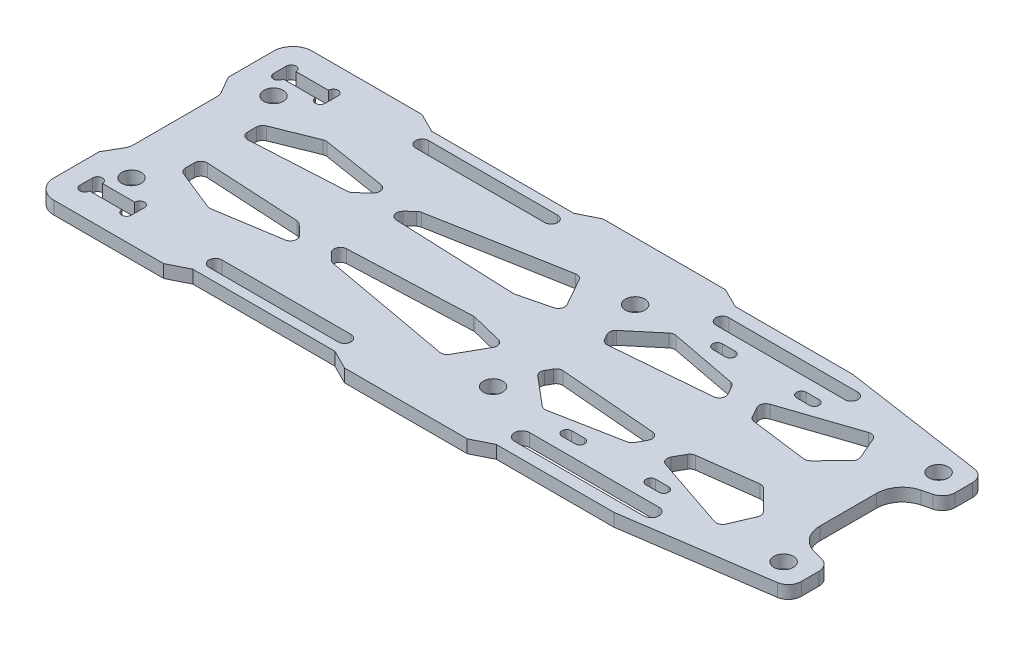
SolidWorks part; units mm, degrees
ref_plane "Front Plane" through (0, 0, 0) normal (0, 0, 1) x (1, 0, 0)
ref_plane "Top Plane" through (0, 0, 0) normal (0, 1, 0) x (1, 0, 0)
ref_plane "Right Plane" through (0, 0, 0) normal (1, 0, 0) x (0, 0, -1)
sketch "Sketch1" plane through (0, 0, 0) normal (0, 1, 0) x (1, 0, 0)
  line L0 (-46.6349, 20) -> (65.3651, 20)
  line L1 (-25.5638, -20) -> (-39.7059, -20)
  line L7 (-40.6349, 17) -> (15.3651, 17) construction
  line L8 (-40.6349, -17) -> (-40.6349, 17) construction
  line L9 (-40.6349, -17) -> (15.3651, -17) construction
  line L10 (15.3651, 17) -> (15.3651, -17) construction
  line L11 (-40.6349, 17) -> (15.3651, -17) construction
  line L12 (-40.6349, -17) -> (15.3651, 17) construction
  line L13 (65.3651, 20) -> (65.3651, -20)
  line L14 (65.3651, -20) -> (-25.5638, -20)
  line L15 (-46.6349, -20) -> (-46.6349, 20)
  line L16 (15.3651, 17) -> (61.3651, 17) construction
  line L17 (61.3651, 17) -> (61.3651, -17) construction
  line L18 (61.3651, -17) -> (15.3651, -17) construction
  line L19 (31.3651, -20) -> (65.3651, -15)
  line L20 (31.3651, 20) -> (65.3651, 15)
  line L21 (-46.6349, -14) -> (-35.6349, -14) construction
  line L22 (-46.6349, 14) -> (-35.6349, 14) construction
  line L23 (-35.6349, -14) -> (-35.6349, -16)
  line L24 (-35.6349, -16) -> (-43.6349, -16)
  line L25 (-43.6349, -16) -> (-43.6349, -14)
  line L30 (-39.7059, -20) -> (-46.6349, -20)
  line L45 (65.3651, -9) -> (59.3651, -7.5)
  line L46 (59.3651, -7.5) -> (59.3651, 7.5)
  line L47 (59.3651, 7.5) -> (65.3651, 9)
  line L48 (-35.6349, 14) -> (-35.6349, 16)
  line L49 (-35.6349, 16) -> (-43.6349, 16)
  line L50 (-43.6349, 16) -> (-43.6349, 14)
  line L51 (-43.6349, -14) -> (-35.6349, -14)
  line L52 (-43.6349, 14) -> (-35.6349, 14)
  line L53 (-44.909, -7) -> (-46.639, -10)
  line L54 (-44.909, 6.998) -> (-46.639, 10)
  line L55 (-44.909, -7) -> (-44.909, 6.998)
  circle A0 centre (15.3651, -11) radius 1.5
  circle A1 centre (15.3651, 11) radius 1.5
  arc A6 (-43.6349, -16) -> (-42.1349, -16) centre (-42.8849, -16) ccw
  arc A7 (-35.6349, -16) -> (-37.1349, -16) centre (-36.3849, -16) cw
  circle A8 centre (61.3651, -12) radius 1.5
  circle A9 centre (61.3651, 12) radius 1.5
  arc A18 (-35.6349, -14) -> (-37.1349, -14) centre (-36.3849, -14) ccw
  arc A19 (-43.6349, -14) -> (-42.1349, -14) centre (-42.8849, -14) cw
  arc A20 (-43.6349, 14) -> (-42.1349, 14) centre (-42.8849, 14) ccw
  arc A21 (-43.6349, 16) -> (-42.1349, 16) centre (-42.8849, 16) cw
  arc A22 (-35.6349, 16) -> (-37.1349, 16) centre (-36.3849, 16) ccw
  arc A23 (-35.6349, 14) -> (-37.1349, 14) centre (-36.3849, 14) cw
  circle A24 centre (-40.6349, -11) radius 1.5
  circle A25 centre (-40.6349, 11) radius 1.5
  point P0 (-12.6349, 0)
  point P5 (-12.6349, 0)
  dimension "D7" = 3
  dimension "D8" = 3
  dimension "D43" = 3
  dimension "D44" = 3
  dimension "D47" = 3
  dimension "D48" = 3
  dimension "D3" = 56
  dimension "D4" = 34
  dimension "D5" = 3
  dimension "D6" = 50
  dimension "D9" = 8
  dimension "D10" = 8
  dimension "D11" = 34
  dimension "D12" = 34
  dimension "D13" = 5
  dimension "D14" = 5
  dimension "D19" = 4
  dimension "D25" = 6
  dimension "D26" = 6
  dimension "D27" = 1.5
  dimension "D28" = 1.5
  dimension "D29" = 6
  dimension "D30" = 40
  dimension "D31" = 28
  dimension "D32" = 6
  dimension "D33" = 8
  dimension "D34" = 2
  dimension "D35" = 3
  dimension "D36" = 8
  dimension "D37" = 3
  dimension "D38" = 2
  dimension "D39" = 1.5
  dimension "D40" = 1.5
  dimension "D41" = 1.5
  dimension "D42" = 1.5
  dimension "D45" = 3
  dimension "D46" = 3
  dimension "D49" = 9
  dimension "D50" = 9
  dimension "D51" = 1
  dimension "D52" = 1
  dimension "D53" = 3.002
  dimension "D54" = 3
extrude "Boss-Extrude1" add sketch "Sketch1" along normal blind 2 contours L55 L53 L15 L30 L1 L14 L19 L13 L45 L46 L47 L20 L0 L54 A25 A24 A9 A8 A1 A0 L25 A19 L51 A18 L23 A7 L24 A6 L48 A23 L52 A20 L50 A21 L49 A22
fillet "Fillet1" radius 3 2 edges at (-46.6349, 1, -20) (-46.6349, 1, 20)
fillet "Fillet2" radius 2 4 edges at (65.3651, 1, -15) (65.3651, 1, -9) (65.3651, 1, 15) (65.3651, 1, 9)
fillet "Fillet3" radius 2 2 edges at (-44.909, 1, 7) (-44.909, 1, -6.998)
fillet "Fillet4" radius 4 2 edges at (59.3651, 1, 7.5) (59.3651, 1, -7.5)
sketch "Sketch3" plane through (0, 2, 0) normal (0, 1, 0) x (1, 0, 0)
  line L0 (-23.6349, 18.5) -> (-1.6349, 18.5)
  line L1 (-23.6349, -18.5) -> (-1.6349, -18.5)
  line L2 (31.3651, -20) -> (-43.6349, -20) construction
  line L3 (-26.6349, 20) -> (-23.6349, 18.5)
  line L4 (-43.6349, 20) -> (31.3651, 20) construction
  line L5 (-1.6349, 18.5) -> (1.3651, 20)
  line L6 (-26.6349, -20) -> (-23.6349, -18.5)
  line L7 (1.3651, -20) -> (-1.6349, -18.5)
  line L8 (-1.6349, -18.5) -> (-1.4114, -18.5)
  line L9 (-35.6349, -14) -> (-35.6349, -16) construction
  line L10 (-35.6349, 14) -> (-35.6349, 16) construction
  line L11 (-22.6349, 16) -> (-2.6349, 16) construction
  line L12 (-22.6349, 17) -> (-2.6349, 17)
  line L13 (-22.6349, 15) -> (-2.6349, 15)
  line L14 (-22.6349, -16) -> (-2.6349, -16) construction
  line L15 (-22.6349, -15) -> (-2.6349, -15)
  line L16 (-22.6349, -17) -> (-2.6349, -17)
  line L17 (23.3651, 18.5) -> (45.3651, 18.5)
  line L18 (23.3651, -18.5) -> (45.3651, -18.5)
  line L19 (20.3651, -20) -> (23.3651, -18.5)
  line L20 (23.3651, 18.5) -> (20.3651, 20)
  line L21 (20.3651, 20) -> (31.3651, 20)
  line L22 (31.3651, 20) -> (41.5651, 18.5)
  line L23 (31.3651, 20) -> (63.6561, 15.2513) construction
  line L24 (20.3651, -20) -> (31.3651, -20)
  line L25 (31.3651, -20) -> (41.5651, -18.5)
  line L26 (24.3651, -15.5) -> (44.3651, -15.5) construction
  line L27 (24.3651, -14.3269) -> (44.3651, -14.3269)
  line L28 (24.3651, -16.6731) -> (44.3651, -16.6731)
  line L29 (24.3651, 15.5) -> (44.3651, 15.5) construction
  line L30 (24.3651, 16.5) -> (44.3651, 16.5)
  line L31 (24.3651, 14.5) -> (44.3651, 14.5)
  line L32 (45.3651, 18.5) -> (41.5651, 18.5)
  line L33 (31.3651, -20) -> (63.6561, -15.2513) construction
  line L34 (41.5651, -18.5) -> (45.3651, -18.5)
  arc A0 (-22.6349, 17) -> (-22.6349, 15) centre (-22.6349, 16) ccw
  arc A1 (-2.6349, 15) -> (-2.6349, 17) centre (-2.6349, 16) ccw
  arc A2 (-22.6349, -15) -> (-22.6349, -17) centre (-22.6349, -16) ccw
  arc A3 (-2.6349, -17) -> (-2.6349, -15) centre (-2.6349, -16) ccw
  arc A4 (24.3651, -14.3269) -> (24.3651, -16.6731) centre (24.3651, -15.5) ccw
  arc A5 (44.3651, -16.6731) -> (44.3651, -14.3269) centre (44.3651, -15.5) ccw
  arc A6 (24.3651, 16.5) -> (24.3651, 14.5) centre (24.3651, 15.5) ccw
  arc A7 (44.3651, 14.5) -> (44.3651, 16.5) centre (44.3651, 15.5) ccw
  point P19 (-12.6349, 16)
  point P24 (-12.6349, -16)
  point P36 (34.3651, -15.5)
  point P52 (34.3651, 15.5)
  line M20 (63.6561, 15.2513) -> (31.3651, 20)
  line M21 (31.3651, 20) -> (-43.6349, 20)
  line M31 (-43.6349, -20) -> (31.3651, -20)
  line M32 (31.3651, -20) -> (63.6561, -15.2513)
  dimension "D12" = 1
  dimension "D14" = 1
  dimension "D1" = 37
  dimension "D2" = 1.5
  dimension "D3" = 12
  dimension "D4" = 12
  dimension "D5" = 3
  dimension "D6" = 3
  dimension "D7" = 3
  dimension "D8" = 3
  dimension "D9" = 22
  dimension "D10" = 22
  dimension "D11" = 2.5
  dimension "D13" = 2.5
  dimension "D15" = 1
  dimension "D16" = 20
  dimension "D17" = 20
  dimension "D18" = 1
  dimension "D19" = 1.5
  dimension "D20" = 3
  dimension "D21" = 3
  dimension "D22" = 25
  dimension "D23" = 22
  dimension "D24" = 22
  dimension "D25" = 25
  dimension "D26" = 3
  dimension "D27" = 1.5
  dimension "D28" = 1
  dimension "D29" = 20
  dimension "D30" = 20
  dimension "D31" = 1
  dimension "D32" = 3
extrude "Cut-Extrude1" cut sketch "Sketch3" against normal through all contours L28 A5 L27 A4 | L34 L18 L19 M32 M31 | L7 L1 L6 M31 | L16 A3 L15 A2 | L17 L32 L20 M20 M21 | L31 A7 L30 A6 | L0 L5 L3 M21 | L13 A1 L12 A0
sketch "Sketch6" plane through (0, 2, 0) normal (0, 1, 0) x (1, 0, 0)
  line L0 (-44.909, -0.0008) -> (59.3651, 0) construction
  line L1 (-44.909, -6.4647) -> (-44.909, 6.463) construction
  line L2 (59.3651, -4.3769) -> (59.3651, 4.3769) construction
  line L3 (-37.787, 3.0551) -> (-21.7169, 3.946)
  line L4 (-21.7169, 3.946) -> (-18.4542, 7.113)
  line L5 (-18.4542, 7.113) -> (-30.6285, 9.0449)
  line L6 (-30.6285, 9.0449) -> (-37.787, 6.1616)
  line L7 (-37.787, 6.1616) -> (-37.787, 3.0551)
  line L8 (-16.794, 3.946) -> (4.531, 3.0551)
  line L9 (4.531, 3.0551) -> (10.7399, 4.5891)
  line L10 (10.7399, 4.5891) -> (7.3326, 10.6474)
  line L11 (7.3326, 10.6474) -> (-13.8645, 6.7896)
  line L12 (-13.8645, 6.7896) -> (-16.794, 3.946)
  line L13 (17.9983, 3.3859) -> (16.7628, 5.5825)
  line L14 (16.7628, 5.5825) -> (22.1762, 10.1271)
  line L15 (22.1762, 10.1271) -> (33.5779, 7.9424)
  line L16 (33.5779, 7.9424) -> (35.3199, 4.8451)
  line L17 (35.3199, 4.8451) -> (17.9983, 3.3859)
  line L18 (37.9995, 7.6872) -> (39.7365, 4.5986)
  line L19 (39.7365, 4.5986) -> (49.5711, 3.3146)
  line L20 (49.5711, 3.3146) -> (53.5623, 7.3433)
  line L21 (53.5623, 7.3433) -> (51.4688, 12.2322)
  line L22 (51.4688, 12.2322) -> (37.9995, 7.6872)
  line L23 (51.469, -12.2323) -> (37.9996, -7.6875)
  line L24 (53.5624, -7.3434) -> (51.469, -12.2323)
  line L25 (49.5712, -3.3148) -> (53.5624, -7.3434)
  line L26 (39.7366, -4.5989) -> (49.5712, -3.3148)
  line L27 (37.9996, -7.6875) -> (39.7366, -4.5989)
  line L28 (35.3199, -4.8455) -> (17.9983, -3.3865)
  line L29 (33.578, -7.9428) -> (35.3199, -4.8455)
  line L30 (22.1763, -10.1277) -> (33.578, -7.9428)
  line L31 (16.7629, -5.5832) -> (22.1763, -10.1277)
  line L32 (17.9983, -3.3865) -> (16.7629, -5.5832)
  line L33 (-13.8644, -6.7907) -> (-16.794, -3.9472)
  line L34 (7.3328, -10.6483) -> (-13.8644, -6.7907)
  line L35 (10.74, -4.5899) -> (7.3328, -10.6483)
  line L36 (4.531, -3.056) -> (10.74, -4.5899)
  line L37 (-16.794, -3.9472) -> (4.531, -3.056)
  line L38 (-37.7869, -6.1631) -> (-37.787, -3.0567)
  line L39 (-30.6284, -9.0463) -> (-37.7869, -6.1631)
  line L40 (-18.4541, -7.1142) -> (-30.6284, -9.0463)
  line L41 (-21.7168, -3.9473) -> (-18.4541, -7.1142)
  line L42 (-37.787, -3.0567) -> (-21.7168, -3.9473)
  line L43 (27.3651, -11.5769) -> (29.3651, -11.5769) construction
  line L44 (27.3651, -10.8269) -> (29.3651, -10.8269)
  line L45 (27.3651, -12.3269) -> (29.3651, -12.3269)
  line L46 (27.3651, 11.75) -> (29.3651, 11.75) construction
  line L47 (27.3651, 12.5) -> (29.3651, 12.5)
  line L48 (27.3651, 11) -> (29.3651, 11)
  line L49 (24.3651, 14.5) -> (44.3651, 14.5) construction
  line L50 (24.3651, -14.3269) -> (44.3651, -14.3269) construction
  line L51 (40.3651, 11.75) -> (42.3651, 11.75) construction
  line L52 (40.3651, 12.5) -> (42.3651, 12.5)
  line L53 (40.3651, 11) -> (42.3651, 11)
  line L54 (40.3651, -11.5769) -> (42.3651, -11.5769) construction
  line L55 (40.3651, -10.8269) -> (42.3651, -10.8269)
  line L56 (40.3651, -12.3269) -> (42.3651, -12.3269)
  arc A0 (27.3651, -10.8269) -> (27.3651, -12.3269) centre (27.3651, -11.5769) ccw
  arc A1 (29.3651, -12.3269) -> (29.3651, -10.8269) centre (29.3651, -11.5769) ccw
  arc A2 (27.3651, 12.5) -> (27.3651, 11) centre (27.3651, 11.75) ccw
  arc A3 (29.3651, 11) -> (29.3651, 12.5) centre (29.3651, 11.75) ccw
  arc A4 (40.3651, 12.5) -> (40.3651, 11) centre (40.3651, 11.75) ccw
  arc A5 (42.3651, 11) -> (42.3651, 12.5) centre (42.3651, 11.75) ccw
  arc A6 (40.3651, -10.8269) -> (40.3651, -12.3269) centre (40.3651, -11.5769) ccw
  arc A7 (42.3651, -12.3269) -> (42.3651, -10.8269) centre (42.3651, -11.5769) ccw
  point P28 (28.3651, -11.5769)
  point P33 (28.3651, 11.75)
  point P68 (41.3651, 11.75)
  point P73 (41.3651, -11.5769)
  dimension "D1" = 0.75
  dimension "D2" = 2
  dimension "D3" = 2
  dimension "D4" = 1.5
  dimension "D5" = 2.75
  dimension "D6" = 2.75
  dimension "D7" = 3
  dimension "D8" = 3
  dimension "D9" = 2
  dimension "D10" = 2
  dimension "D11" = 1.5
  dimension "D12" = 1.5
  dimension "D13" = 2
  dimension "D14" = 2
extrude "Cut-Extrude2" cut sketch "Sketch6" against normal through all contours L6 L7 L3 L4 L5 | L11 L12 L8 L9 L10 | L37 L33 L34 L35 L36 | L42 L38 L39 L40 L41 | L17 L16 L15 L14 L13 | L28 L32 L31 L30 L29 | L27 L23 L24 L25 L26 | L21 L22 L18 L19 L20 | L53 A5 L52 A4 | L48 A3 L47 A2 | L45 A1 L44 A0 | L56 A7 L55 A6
fillet "Fillet5" radius 1 40 edges at (51.4688, 1, -12.2322) (53.5623, 1, -7.3433) (49.5711, 1, -3.3146) (39.7365, 1, -4.5986) (37.9995, 1, -7.6872) (22.1762, 1, -10.1271) (33.5779, 1, -7.9424) (35.3199, 1, -4.8451) (17.9983, 1, -3.3859) (16.7628, 1, -5.5825) (51.469, 1, 12.2323) (53.5624, 1, 7.3434) (49.5712, 1, 3.3148) (39.7366, 1, 4.5989) (37.9996, 1, 7.6875) (35.3199, 1, 4.8455) (33.578, 1, 7.9428) (22.1763, 1, 10.1277) (17.9983, 1, 3.3865) (16.7629, 1, 5.5832) (7.3328, 1, 10.6483) (10.74, 1, 4.5899) (4.531, 1, 3.056) (-13.8644, 1, 6.7907) (-16.794, 1, 3.9472) (-16.794, 1, -3.946) (-13.8645, 1, -6.7896) (7.3326, 1, -10.6474) (4.531, 1, -3.0551) (10.7399, 1, -4.5891) (-21.7168, 1, 3.9473) (-18.4541, 1, 7.1142) (-30.6284, 1, 9.0463) (-37.7869, 1, 6.1631) (-37.787, 1, 3.0567) (-37.787, 1, -3.0551) (-21.7169, 1, -3.946) (-18.4542, 1, -7.113) (-30.6285, 1, -9.0449) (-37.787, 1, -6.1616)
